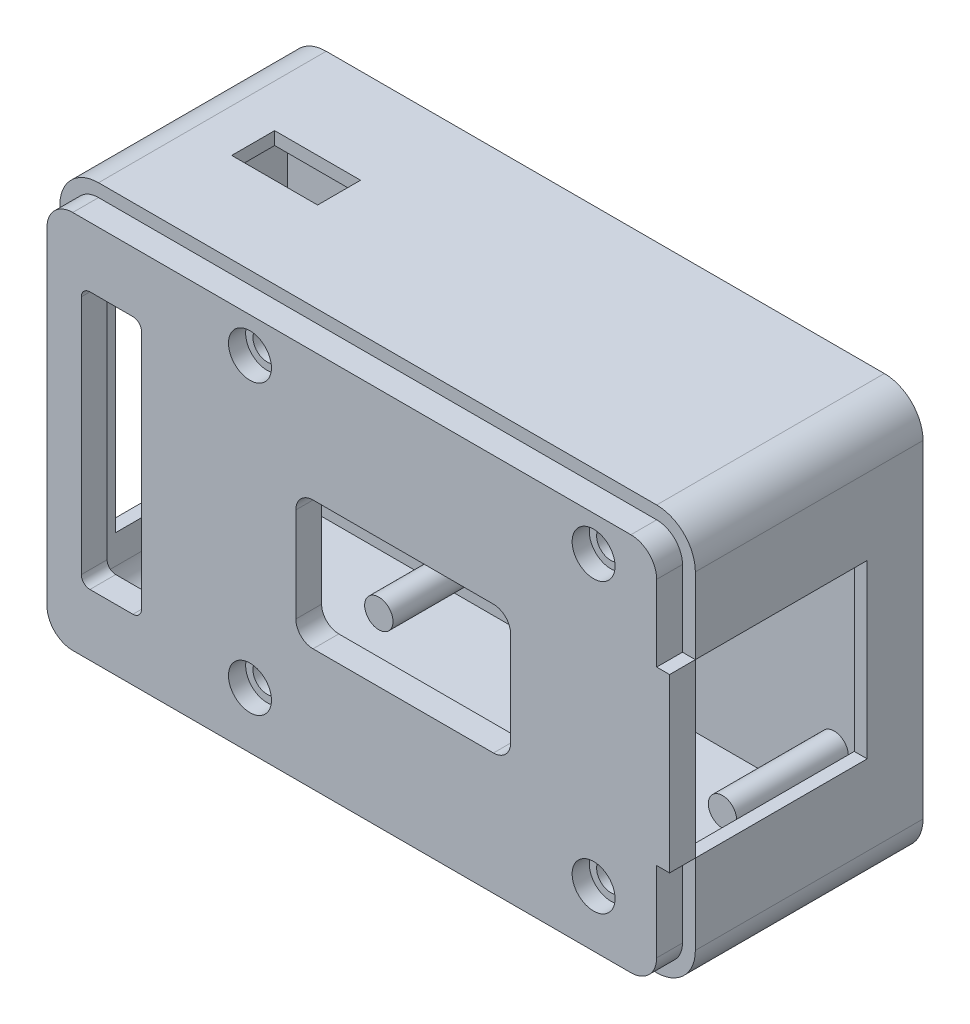
SolidWorks part; units mm, degrees
ref_plane "前视基准面" through (0, 0, 0) normal (0, 0, 1) x (1, 0, 0)
ref_plane "上视基准面" through (0, 0, 0) normal (0, 1, 0) x (1, 0, 0)
ref_plane "右视基准面" through (0, 0, 0) normal (1, 0, 0) x (0, 0, -1)
other "图形1"
other "图形 (闭合) -1"
sketch "草图1" plane through (0, 0, 0) normal (0, 0, 1) x (1, 0, 0)
  line L0 (-64.1233, 1.1291) -> (0.8423, 1.1291)
  line L5 (-64.1233, 2.6291) -> (0.8423, 2.6291)
  line L6 (5.3423, -1.8709) -> (5.3423, -40.0233)
  line L7 (3.8423, -1.8709) -> (3.8423, -40.0233)
  line L8 (-64.1233, -43.0233) -> (0.8423, -43.0233)
  line L9 (-67.1233, -1.8709) -> (-67.1233, -40.0233)
  line L10 (-64.1233, -44.5233) -> (0.8423, -44.5233)
  line L11 (-68.6233, -1.8709) -> (-68.6233, -40.0233)
  arc A0 (3.8423, -40.0233) -> (0.8423, -43.0233) centre (0.8423, -40.0233) cw
  arc A1 (-64.1233, -43.0233) -> (-67.1233, -40.0233) centre (-64.1233, -40.0233) cw
  arc A2 (-64.1233, 1.1291) -> (-67.1233, -1.8709) centre (-64.1233, -1.8709) ccw
  arc A3 (0.8423, 1.1291) -> (3.8423, -1.8709) centre (0.8423, -1.8709) cw
  arc A4 (0.8423, 2.6291) -> (5.3423, -1.8709) centre (0.8423, -1.8709) cw
  arc A5 (5.3423, -40.0233) -> (0.8423, -44.5233) centre (0.8423, -40.0233) cw
  arc A6 (-64.1233, -44.5233) -> (-68.6233, -40.0233) centre (-64.1233, -40.0233) cw
  arc A7 (-64.1233, 2.6291) -> (-68.6233, -1.8709) centre (-64.1233, -1.8709) ccw
  point P0 (-32.0058, -20.9471)
  dimension "D1" = 3
  dimension "D2" = 1.5
extrude "凸台-拉伸3" add sketch "草图1" against normal blind 25
sketch "草图2" plane through (0, 0, -25) normal (0, 0, -1) x (-1, 0, 0)
  line L4 (64.1233, 2.6291) -> (-0.8423, 2.6291)
  line L5 (-5.3423, -1.8709) -> (-5.3423, -40.0233)
  line L6 (-0.8423, -44.5233) -> (64.1233, -44.5233)
  line L7 (68.6233, -40.0233) -> (68.6233, -1.8709)
  line L8 (64.1233, 2.6291) -> (-0.8423, 2.6291)
  line L9 (-5.3423, -1.8709) -> (-5.3423, -40.0233)
  line L10 (-0.8423, -44.5233) -> (64.1233, -44.5233)
  line L11 (68.6233, -40.0233) -> (68.6233, -1.8709)
  arc A4 (68.6233, -1.8709) -> (64.1233, 2.6291) centre (64.1233, -1.8709) ccw
  arc A5 (-0.8423, 2.6291) -> (-5.3423, -1.8709) centre (-0.8423, -1.8709) ccw
  arc A6 (-5.3423, -40.0233) -> (-0.8423, -44.5233) centre (-0.8423, -40.0233) ccw
  arc A7 (64.1233, -44.5233) -> (68.6233, -40.0233) centre (64.1233, -40.0233) ccw
  arc A8 (68.6233, -1.8709) -> (64.1233, 2.6291) centre (64.1233, -1.8709) ccw
  arc A9 (-0.8423, 2.6291) -> (-5.3423, -1.8709) centre (-0.8423, -1.8709) ccw
  arc A10 (-5.3423, -40.0233) -> (-0.8423, -44.5233) centre (-0.8423, -40.0233) ccw
  arc A11 (64.1233, -44.5233) -> (68.6233, -40.0233) centre (64.1233, -40.0233) ccw
  dimension "D1" = 0
extrude "凸台-拉伸4" add sketch "草图2" along normal blind 1.5 contours A8 L8 A9 L9 A10 L10 A11 L11
sketch "草图3" plane through (0, 0, -25) normal (0, 0, 1) x (1, 0, 0)
  circle A0 centre (-43.4992, -2.9755) radius 1.65
  circle A1 centre (-3.4992, -2.9755) radius 1.65
  circle A2 centre (-3.4992, -36.4755) radius 1.65
  circle A3 centre (-43.4992, -36.4755) radius 1.65
  dimension "D1" = 2
  dimension "D2" = 2
extrude "凸台-拉伸6" add sketch "草图3" along normal blind 13
sketch "草图4" plane through (-67.1233, 0, 0) normal (1, 0, 0) x (0, 0, -1)
  line L0 (25, -1.8709) -> (25, -40.0233) construction
  line L1 (5, -6.6397) -> (15, -6.6397)
  line L2 (5, -6.6397) -> (5, -36.6397)
  line L3 (5, -36.6397) -> (15, -36.6397)
  line L4 (15, -6.6397) -> (15, -36.6397)
  line L5 (5, -6.6397) -> (15, -36.6397) construction
  line L6 (5, -36.6397) -> (15, -6.6397) construction
  point P0 (10, -21.6397)
  point P5 (13.5186, -21.6397)
  dimension "D1" = 30
  dimension "D2" = 10
  dimension "D3" = 10
extrude "切除-拉伸1" cut sketch "草图4" against normal up to next
sketch "草图5" plane through (3.8423, 0, 0) normal (-1, 0, 0) x (0, 0, 1)
  line L0 (-25, -40.0233) -> (-25, -1.8709) construction
  line L1 (-20, -10.7139) -> (0, -10.7139)
  line L2 (-20, -10.7139) -> (-20, -30.7139)
  line L3 (-20, -30.7139) -> (0, -30.7139)
  line L4 (0, -10.7139) -> (0, -30.7139)
  line L5 (-20, -10.7139) -> (0, -30.7139) construction
  line L6 (-20, -30.7139) -> (0, -10.7139) construction
  point P0 (-10, -20.7139)
  dimension "D1" = 20
  dimension "D2" = 20
  dimension "D3" = 5
extrude "切除-拉伸2" cut sketch "草图5" against normal up to next
sketch "草图6" plane through (0, 2.6291, 0) normal (0, 1, 0) x (1, 0, 0)
  line L0 (-64.1233, 26.5) -> (0.8423, 26.5) construction
  line L1 (-59.1233, 15.5) -> (-49.1233, 15.5)
  line L2 (-59.1233, 15.5) -> (-59.1233, 10.5)
  line L3 (-59.1233, 10.5) -> (-49.1233, 10.5)
  line L4 (-49.1233, 15.5) -> (-49.1233, 10.5)
  line L5 (-59.1233, 15.5) -> (-49.1233, 10.5) construction
  line L6 (-59.1233, 10.5) -> (-49.1233, 15.5) construction
  line L7 (-64.1233, 26.5) -> (-64.1233, 0) construction
  point P0 (-54.1233, 13)
  dimension "D1" = 10
  dimension "D2" = 5
  dimension "D3" = 11
  dimension "D4" = 5
extrude "切除-拉伸3" cut sketch "草图6" against normal up to next
sketch "草图7" plane through (0, 0, 0) normal (0, 0, 1) x (1, 0, 0)
  line L0 (0.8423, 1.1291) -> (-64.1233, 1.1291) construction
  line L1 (0.8423, 1.1291) -> (-64.1233, 1.1291)
  line L2 (-64.1233, -43.0233) -> (0.8423, -43.0233) construction
  line L3 (-64.1233, -43.0233) -> (0.8423, -43.0233)
  line L5 (5.3423, -10.7139) -> (5.3423, -30.7139)
  line L16 (5.3423, -30.7139) -> (3.8423, -30.7139)
  line L17 (3.8423, -30.7139) -> (3.8423, -40.0233)
  line L18 (0.8423, -43.0233) -> (-64.1233, -43.0233)
  line L19 (-67.1233, -40.0233) -> (-67.1233, -1.8709)
  line L20 (-64.1233, 1.1291) -> (0.8423, 1.1291)
  line L21 (3.8423, -1.8709) -> (3.8423, -10.7139)
  line L22 (3.8423, -10.7139) -> (5.3423, -10.7139)
  line L23 (5.3423, -10.7139) -> (5.3423, -1.8709)
  line L24 (0.8423, 2.6291) -> (-64.1233, 2.6291)
  line L25 (-68.6233, -1.8709) -> (-68.6233, -40.0233)
  line L26 (-64.1233, -44.5233) -> (0.8423, -44.5233)
  line L27 (5.3423, -40.0233) -> (5.3423, -30.7139)
  line L28 (5.3423, -30.7139) -> (3.8423, -30.7139)
  line L29 (3.8423, -30.7139) -> (3.8423, -40.0233)
  line L30 (0.8423, -43.0233) -> (-64.1233, -43.0233)
  line L31 (-67.1233, -40.0233) -> (-67.1233, -1.8709)
  line L32 (-64.1233, 1.1291) -> (0.8423, 1.1291)
  line L33 (3.8423, -1.8709) -> (3.8423, -10.7139)
  line L34 (3.8423, -10.7139) -> (5.3423, -10.7139)
  arc A8 (0.8423, -43.0233) -> (3.8423, -40.0233) centre (0.8423, -40.0233) ccw
  arc A9 (-67.1233, -40.0233) -> (-64.1233, -43.0233) centre (-64.1233, -40.0233) ccw
  arc A10 (-64.1233, 1.1291) -> (-67.1233, -1.8709) centre (-64.1233, -1.8709) ccw
  arc A11 (3.8423, -1.8709) -> (0.8423, 1.1291) centre (0.8423, -1.8709) ccw
  arc A12 (5.3423, -1.8709) -> (0.8423, 2.6291) centre (0.8423, -1.8709) ccw
  arc A13 (-64.1233, 2.6291) -> (-68.6233, -1.8709) centre (-64.1233, -1.8709) ccw
  arc A14 (-68.6233, -40.0233) -> (-64.1233, -44.5233) centre (-64.1233, -40.0233) ccw
  arc A15 (0.8423, -44.5233) -> (5.3423, -40.0233) centre (0.8423, -40.0233) ccw
  arc A16 (0.8423, -43.0233) -> (3.8423, -40.0233) centre (0.8423, -40.0233) ccw
  arc A17 (-67.1233, -40.0233) -> (-64.1233, -43.0233) centre (-64.1233, -40.0233) ccw
  arc A18 (-64.1233, 1.1291) -> (-67.1233, -1.8709) centre (-64.1233, -1.8709) ccw
  arc A19 (3.8423, -1.8709) -> (0.8423, 1.1291) centre (0.8423, -1.8709) ccw
  line M22 (5.3423, -30.7139) -> (3.8423, -30.7139)
  line M23 (3.8423, -30.7139) -> (3.8423, -40.0233)
  arc M24 (3.8423, -40.0233) -> (0.8423, -43.0233) centre (0.8423, -40.0233) cw
  line M25 (0.8423, -43.0233) -> (-64.1233, -43.0233)
  arc M26 (-64.1233, -43.0233) -> (-67.1233, -40.0233) centre (-64.1233, -40.0233) cw
  line M27 (-67.1233, -40.0233) -> (-67.1233, -1.8709)
  arc M28 (-67.1233, -1.8709) -> (-64.1233, 1.1291) centre (-64.1233, -1.8709) cw
  line M29 (-64.1233, 1.1291) -> (0.8423, 1.1291)
  arc M30 (0.8423, 1.1291) -> (3.8423, -1.8709) centre (0.8423, -1.8709) cw
  line M31 (3.8423, -1.8709) -> (3.8423, -10.7139)
  line M32 (3.8423, -10.7139) -> (5.3423, -10.7139)
  dimension "D1" = 0
extrude "凸台-拉伸7" add sketch "草图7" along normal blind 3 separate body contours L5 M32 M31 M30 M29 M28 M27 M26 M25 M24 M23 M22
sketch "草图8" plane through (0, 0, 3) normal (0, 0, 1) x (1, 0, 0)
  circle A1 centre (-43.4992, -2.9755) radius 1.65
  circle A2 centre (-43.4992, -2.9755) radius 1.65
  circle A3 centre (-43.4992, -36.4755) radius 1.65
  circle A12 centre (-43.4992, -36.4755) radius 1.65
  circle A13 centre (-3.4992, -2.9755) radius 1.65
  circle A14 centre (-3.4992, -2.9755) radius 1.65
  circle A15 centre (-3.4992, -36.4755) radius 1.65
  circle A16 centre (-3.4992, -36.4755) radius 1.65
  dimension "D2" = 0
  dimension "D3" = 0
  dimension "D4" = 0
  dimension "D5" = 0
extrude "切除-拉伸5" cut sketch "草图8" against normal up to next (3 mm away)
sketch "草图9" plane through (0, 0, 3) normal (0, 0, 1) x (1, 0, 0)
  line L0 (-49.1233, 1.1291) -> (-59.1233, 1.1291) construction
  line L1 (-62.1233, -5.8709) -> (-57.1233, -5.8709)
  line L2 (-63.1233, -6.8709) -> (-63.1233, -34.8709)
  line L3 (-62.1233, -35.8709) -> (-57.1233, -35.8709)
  line L4 (-56.1233, -6.8709) -> (-56.1233, -34.8709)
  line L5 (-63.1233, -5.8709) -> (-56.1233, -35.8709) construction
  line L6 (-63.1233, -35.8709) -> (-56.1233, -5.8709) construction
  line L7 (-67.1233, -40.0233) -> (-67.1233, -1.8709) construction
  arc A0 (-57.1233, -35.8709) -> (-56.1233, -34.8709) centre (-57.1233, -34.8709) ccw
  arc A1 (-63.1233, -34.8709) -> (-62.1233, -35.8709) centre (-62.1233, -34.8709) ccw
  arc A2 (-57.1233, -5.8709) -> (-56.1233, -6.8709) centre (-57.1233, -6.8709) cw
  arc A3 (-62.1233, -5.8709) -> (-63.1233, -6.8709) centre (-62.1233, -6.8709) ccw
  point P0 (-59.6233, -20.8709)
  dimension "D3" = 1
  dimension "D1" = 30
  dimension "D2" = 7
  dimension "D4" = 7
  dimension "D5" = 4
extrude "切除-拉伸6" cut sketch "草图9" against normal up to next (3 mm away)
sketch "草图10" plane through (0, 0, 3) normal (0, 0, 1) x (1, 0, 0)
  line L0 (-64.1233, 1.1291) -> (0.8423, 1.1291) construction
  line L1 (-36.1577, -13.8709) -> (-15.1577, -13.8709)
  line L2 (-38.1577, -15.8709) -> (-38.1577, -26.8709)
  line L3 (-36.1577, -28.8709) -> (-15.1577, -28.8709)
  line L4 (-13.1577, -15.8709) -> (-13.1577, -26.8709)
  line L5 (-38.1577, -13.8709) -> (-13.1577, -28.8709) construction
  line L6 (-38.1577, -28.8709) -> (-13.1577, -13.8709) construction
  line L7 (3.8423, -1.8709) -> (3.8423, -10.7139) construction
  arc A0 (-15.1577, -28.8709) -> (-13.1577, -26.8709) centre (-15.1577, -26.8709) ccw
  arc A1 (-15.1577, -13.8709) -> (-13.1577, -15.8709) centre (-15.1577, -15.8709) cw
  arc A2 (-38.1577, -26.8709) -> (-36.1577, -28.8709) centre (-36.1577, -26.8709) ccw
  arc A3 (-36.1577, -13.8709) -> (-38.1577, -15.8709) centre (-36.1577, -15.8709) ccw
  point P0 (-25.6577, -21.3709)
  dimension "D5" = 2
  dimension "D1" = 15
  dimension "D2" = 25
  dimension "D3" = 15
  dimension "D4" = 17
extrude "切除-拉伸7" cut sketch "草图10" against normal up to next (3 mm away)
sketch "草图11" plane through (0, 0, 3) normal (0, 0, 1) x (1, 0, 0)
  circle A12 centre (-3.4992, -36.4755) radius 2.5
  circle A13 centre (-3.4992, -2.9755) radius 2.5
  circle A14 centre (-43.4992, -2.9755) radius 2.5
  circle A15 centre (-43.4992, -36.4755) radius 2.5
extrude "切除-拉伸8" cut sketch "草图11" against normal blind 2
